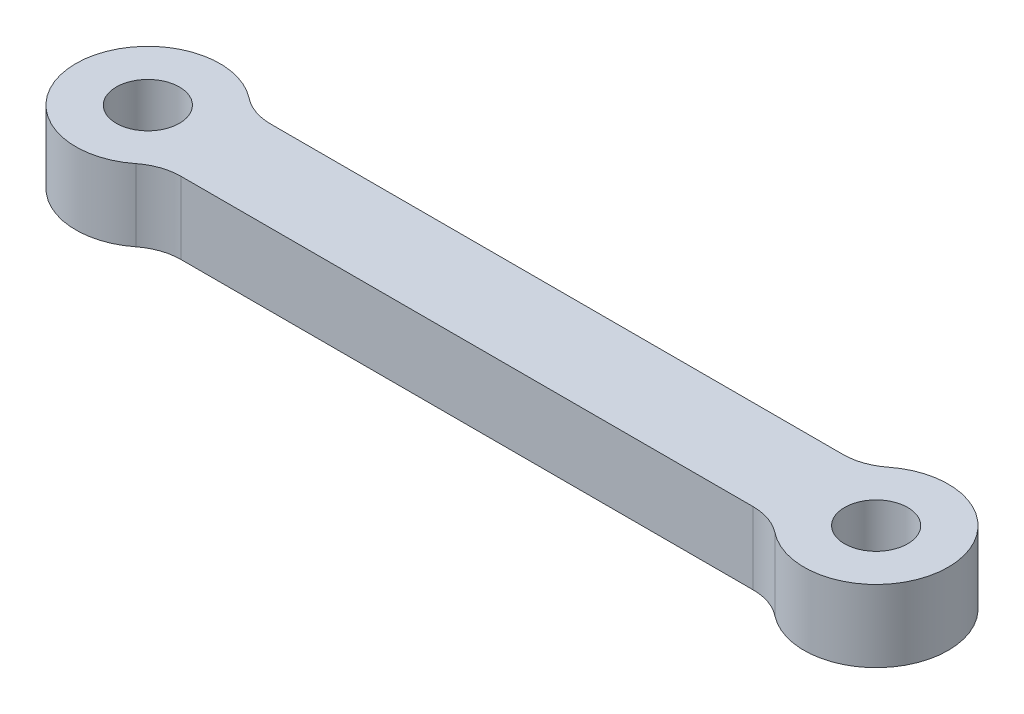
SolidWorks part; units mm, degrees
ref_plane "Front Plane" through (0, 0, 0) normal (0, 0, 1) x (1, 0, 0)
ref_plane "Top Plane" through (0, 0, 0) normal (0, 1, 0) x (1, 0, 0)
ref_plane "Right Plane" through (0, 0, 0) normal (1, 0, 0) x (0, 0, -1)
ref_plane "Plane1" through (0, 0, 0) normal (0, -1, 0) x (1, 0, 0)
sketch "Sketch1" plane through (0, 0, 0) normal (0, -1, 0) x (1, 0, 0)
  line L0 (36.0799, 2.5) -> (4.3301, 2.5)
  line L1 (4.3301, -2.5) -> (36.0799, -2.5)
  circle A0 centre (40.41, 0) radius 1.75
  circle A1 centre (0, 0) radius 1.75
  arc A2 (37.9356, 3.1429) -> (36.0799, 2.5) centre (36.0799, 5.5) cw
  arc A3 (4.3301, 2.5) -> (2.4744, 3.1429) centre (4.3301, 5.5) cw
  arc A4 (2.4744, 3.1429) -> (2.4744, -3.1429) centre (0, 0) ccw
  arc A5 (2.4744, -3.1429) -> (4.3301, -2.5) centre (4.3301, -5.5) cw
  arc A6 (36.0799, -2.5) -> (37.9356, -3.1429) centre (36.0799, -5.5) cw
  arc A7 (37.9356, -3.1429) -> (37.9356, 3.1429) centre (40.41, 0) ccw
  dimension "D1" = 3.5
  dimension "D2" = 3
  dimension "D3" = 4
  dimension "D4" = 2.4744
  dimension "D5" = 36.0799
extrude "Boss-Extrude1" add sketch "Sketch1" against normal blind 4
